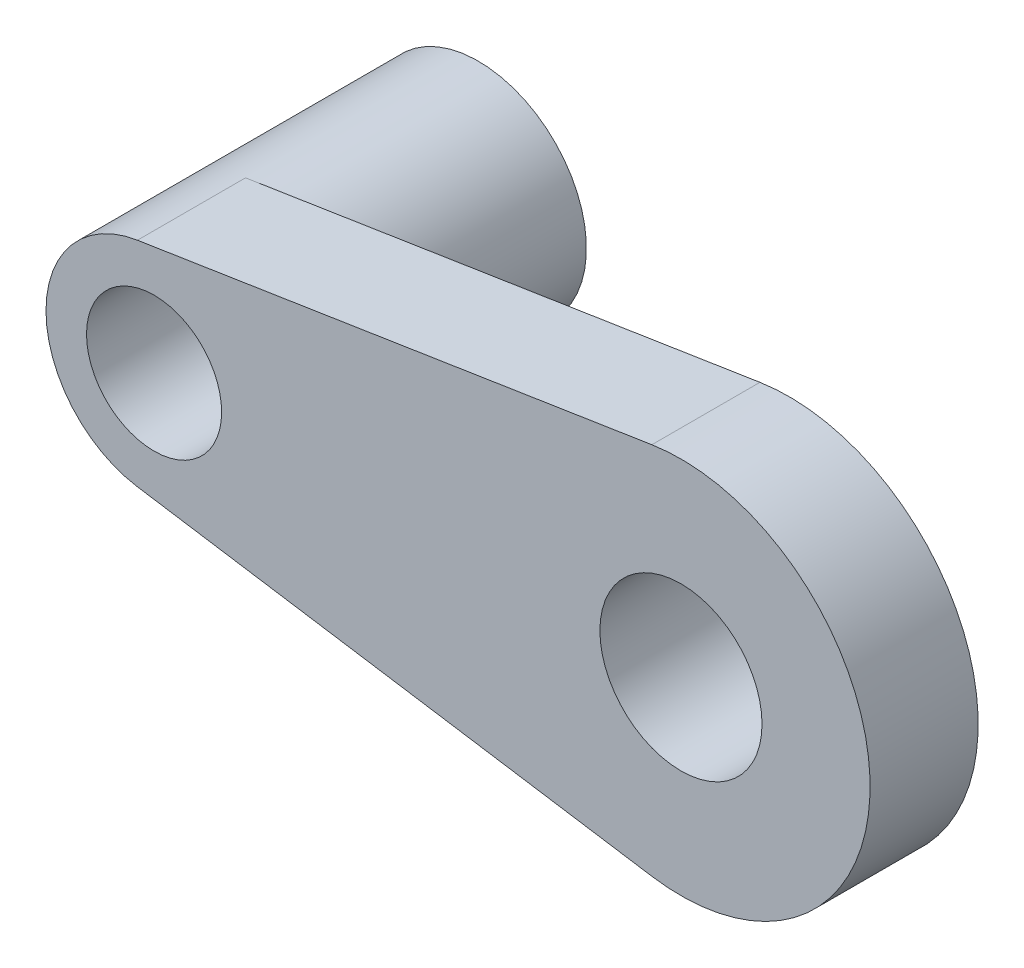
SolidWorks part; units mm, degrees
ref_plane "Plan de face" through (0, 0, 0) normal (0, 0, 1) x (1, 0, 0)
ref_plane "Plan de dessus" through (0, 0, 0) normal (0, 1, 0) x (1, 0, 0)
ref_plane "Plan de droite" through (0, 0, 0) normal (1, 0, 0) x (0, 0, -1)
sketch "Esquisse1" plane through (0, 0, 0) normal (0, 0, 1) x (1, 0, 0)
  line L0 (-10.0577, 1.9762) -> (-0.5385, 3.4583)
  line L1 (-10.0577, -1.9762) -> (-0.5385, -3.4583)
  circle A0 centre (0, 0) radius 1.5
  circle A1 centre (-9.75, 0) radius 1.25
  arc A2 (-0.5385, -3.4583) -> (-0.5385, 3.4583) centre (0, 0) ccw
  arc A3 (-10.0577, 1.9762) -> (-10.0577, -1.9762) centre (-9.75, 0) ccw
  point P11 (-1.9532, -2.9043)
  point P12 (-8.9029, -3.1377)
  point P13 (-8.6401, 3.0546)
  point P14 (-1.7086, 3.0546)
  dimension "D1" = 3
  dimension "D3" = 2.5
  dimension "D4" = 4
  dimension "D5" = 7
  dimension "D2" = 9.75
extrude "Boss.-Extru.1" add sketch "Esquisse1" along normal blind 2
sketch "Esquisse2" plane through (0, 0, 0) normal (0, 0, -1) x (-1, 0, 0)
  circle A0 centre (9.75, 0) radius 1.25
  circle A2 centre (9.75, 0) radius 2
extrude "Boss.-Extru.2" add sketch "Esquisse2" along normal blind 4
sketch "Esquisse3" plane through (0, 0, 0) normal (0, 0, -1) x (-1, 0, 0)
  circle A3 centre (0, 0) radius 1.75
  circle A4 centre (0, 0) radius 1.5
  dimension "D1" = 3.5
extrude "Boss.-Extru.3" add sketch "Esquisse3" along normal blind 0.5
